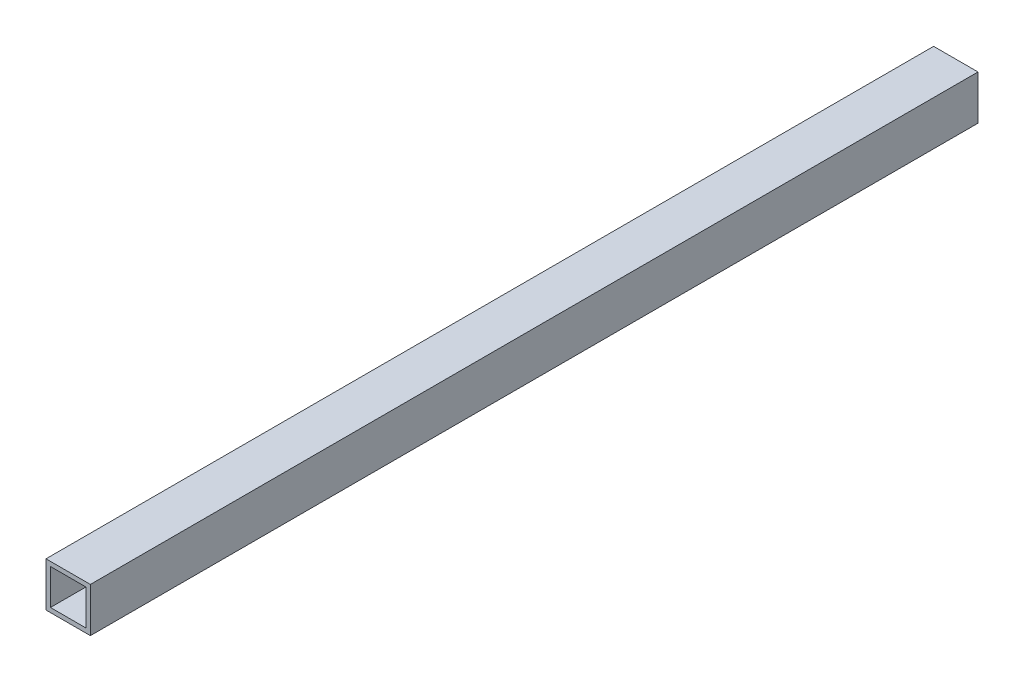
SolidWorks part; units mm, degrees
ref_plane "前视基准面" through (0, 0, 0) normal (0, 0, 1) x (1, 0, 0)
ref_plane "上视基准面" through (0, 0, 0) normal (0, 1, 0) x (1, 0, 0)
ref_plane "右视基准面" through (0, 0, 0) normal (1, 0, 0) x (0, 0, -1)
sketch "草图1" plane through (0, 0, 0) normal (0, 0, 1) x (1, 0, 0)
  line L1 (-6, 6) -> (6, 6)
  line L2 (-6, 6) -> (-6, -6)
  line L3 (-6, -6) -> (6, -6)
  line L4 (6, 6) -> (6, -6)
  line L5 (-6, 6) -> (6, -6) construction
  line L6 (-6, -6) -> (6, 6) construction
  point P0 (0, 0)
  dimension "D1" = 12
extrude "拉伸-薄壁1" add sketch "草图1" along normal blind 300 thin thin type one direction wall 1.5
